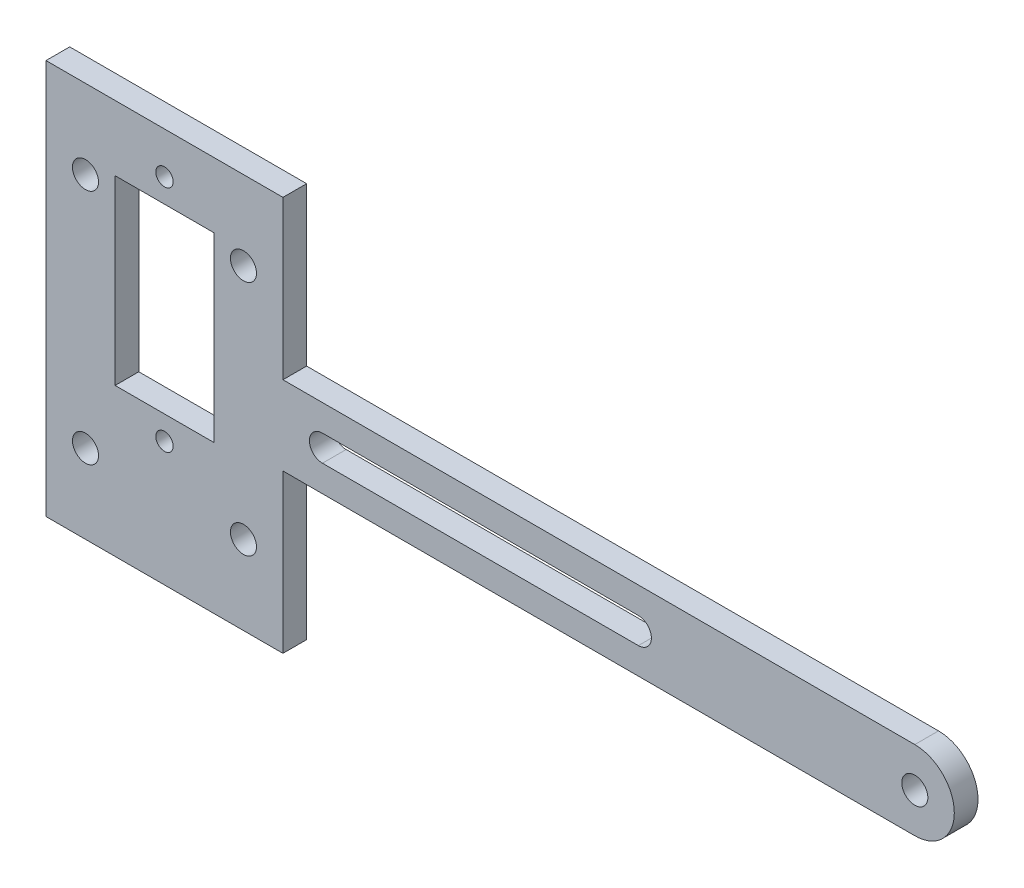
SolidWorks part; units mm, degrees
ref_plane "前视基准面" through (0, 0, 0) normal (0, 0, 1) x (1, 0, 0)
ref_plane "上视基准面" through (0, 0, 0) normal (0, 1, 0) x (1, 0, 0)
ref_plane "右视基准面" through (0, 0, 0) normal (1, 0, 0) x (0, 0, -1)
sketch "草图1" plane through (0, 0, 0) normal (0, 0, 1) x (1, 0, 0)
  line L0 (6.25, -6.25) -> (6.25, 16.75)
  line L1 (6.25, 16.75) -> (-6.25, 16.75)
  line L2 (-6.25, 16.75) -> (-6.25, -6.25)
  line L3 (-6.25, -6.25) -> (6.25, -6.25)
  line L4 (15, -25) -> (15, -5)
  line L5 (15, 25) -> (-15, 25)
  line L6 (-15, 25) -> (-15, -25)
  line L7 (-15, -25) -> (15, -25)
  line L8 (15, 0) -> (51.8461, 0) construction
  line L9 (15, -5) -> (95, -5)
  line L10 (95, 5) -> (15, 5)
  line L11 (20, -1.65) -> (60, -1.65)
  line L12 (20, 1.65) -> (60, 1.65)
  line L13 (15, 5) -> (15, 25)
  circle A0 centre (0, 19.75) radius 1.1
  circle A1 centre (0, -9.25) radius 1.1
  arc A2 (95, -5) -> (95, 5) centre (95, 0) ccw
  arc A3 (20, -1.65) -> (20, 1.65) centre (20, 0) cw
  arc A4 (60, 1.65) -> (60, -1.65) centre (60, 0) cw
  circle A5 centre (95, 0) radius 1.65
  circle A6 centre (10, 15) radius 1.65
  circle A7 centre (-10, 15) radius 1.65
  circle A8 centre (10, -15) radius 1.65
  circle A9 centre (-10, -15) radius 1.65
  point P0 (6.25, -6.25)
  point P6 (15, -25)
  point P7 (6.25, -6.25)
  point P9 (6.75, 16.75)
  point P24 (20, 0)
  dimension "D5" = 80
  dimension "D6" = 2
  dimension "D7" = 3.3
  dimension "D8" = 2.2
  dimension "D1" = 12.5
  dimension "D3" = 50
  dimension "D4" = 30
extrude "凸台-拉伸1" add sketch "草图1" along normal blind 3
